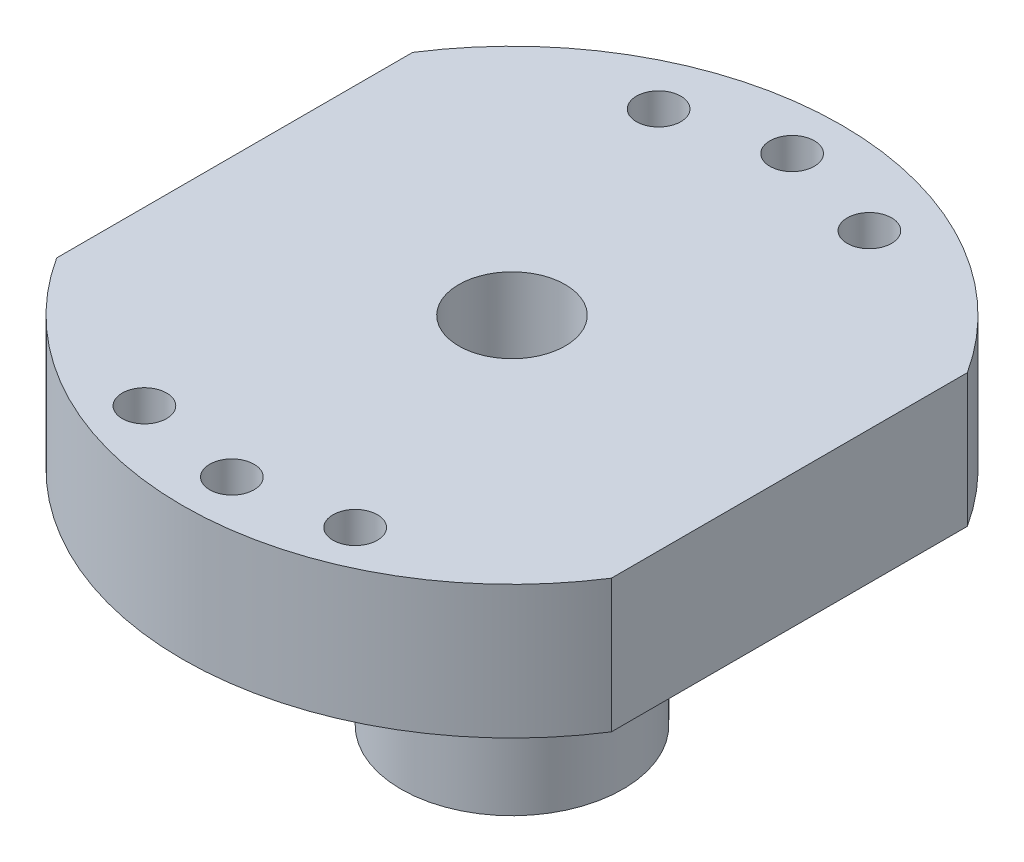
SolidWorks part; units mm, degrees
ref_plane "Front Plane" through (0, 0, 0) normal (0, 0, 1) x (1, 0, 0)
ref_plane "Top Plane" through (0, 0, 0) normal (0, 1, 0) x (1, 0, 0)
ref_plane "Right Plane" through (0, 0, 0) normal (1, 0, 0) x (0, 0, -1)
sketch "Sketch1" plane through (0, -18, 0) normal (0, -1, 0) x (1, 0, 0)
  line L1 (-23.4533, -87.6601) -> (26.5467, -87.6601)
  line L2 (-23.4533, -87.6601) -> (-23.4533, 12.3399)
  line L3 (-23.4533, 12.3399) -> (26.5467, 12.3399)
  line L4 (26.5467, -87.6601) -> (26.5467, 12.3399)
  circle A0 centre (1.5467, -37.6601) radius 29.705
  circle A1 centre (1.5467, -37.6601) radius 29.705 construction
  point P9 (1.5467, 12.3399)
  point P10 (-23.4533, -37.6601)
  circle M1 centre (-7.9533, -14.0266) radius 2
  circle M2 centre (11.0467, -14.0266) radius 2
  circle M3 centre (11.0467, -60.3766) radius 2
  circle M4 centre (-7.9533, -60.3766) radius 2
  circle M5 centre (1.5467, -62.9101) radius 2
  circle M6 centre (1.5467, -12.4101) radius 2
  line M11 (-13.578, -51.1251) -> (-13.578, -45.6601)
  line M12 (-13.578, -45.6601) -> (-17.0561, -45.6601)
  arc M13 (-17.0561, -45.6601) -> (-17.0561, -29.6601) centre (1.5467, -37.6601) cw
  line M14 (-17.0561, -29.6601) -> (-13.578, -29.6601)
  line M15 (-13.578, -29.6601) -> (-13.578, -24.1951)
  arc M16 (-13.578, -24.1951) -> (16.6713, -24.1951) centre (1.5467, -37.6601) cw
  line M17 (16.6713, -24.1951) -> (16.6713, -29.6601)
  line M18 (16.6713, -29.6601) -> (20.1494, -29.6601)
  line M19 (20.1494, -29.6601) -> (20.1494, -32.6601)
  line M20 (20.1494, -32.6601) -> (16.6713, -32.6601)
  line M21 (16.6713, -32.6601) -> (16.6713, -42.6601)
  line M22 (16.6713, -42.6601) -> (20.1494, -42.6601)
  line M23 (20.1494, -42.6601) -> (20.1494, -45.6601)
  line M24 (20.1494, -45.6601) -> (16.6713, -45.6601)
  line M25 (16.6713, -45.6601) -> (16.6713, -51.1251)
  arc M26 (16.6713, -51.1251) -> (-13.578, -51.1251) centre (1.5467, -37.6601) cw
  dimension "D1" = 50
  dimension "D2" = 100
extrude "Boss-Extrude1" add sketch "Sketch1" along normal blind 12 contours L4 A0 L2 M1 M3 M5 M26 M11 M12 M13 M14 M15 M16 M17 M18 M19 M20 M21 M22 M23 M24 M25 M6 M4 M2 | M11 M26 M25 M24 M23 M22 M21 M20 M19 M18 M17 M16 M15 M14 M13 M12
sketch "Sketch2" plane through (0, -30, 0) normal (0, -1, 0) x (1, 0, 0)
  circle A0 centre (1.5467, -37.6601) radius 4.8
  circle A1 centre (1.5467, -37.6601) radius 4.8 construction
extrude "Cut-Extrude1" cut sketch "Sketch2" against normal through all
sketch3d "3DSketch1"
  line L0 (1.5467, -30, -37.6601) -> (1.5467, -78.1853, -37.6601) construction
  line L1 (1.5467, -18, -37.6601) -> (1.5467, -30, -37.6601) construction
  line L2 (1.5467, -30, -37.6601) -> (1.5467, -30, 3.5909) construction
  line L3 (1.5467, -30, -32.8601) -> (1.5467, -45, -32.8601)
  line L4 (1.5467, -45, -32.8601) -> (1.5467, -45, -33.1601)
  line L5 (1.5467, -45, -33.1601) -> (1.5467, -50, -33.1601)
  line L7 (1.5467, -50, -33.1601) -> (1.5467, -50, -27.6601)
  line L8 (1.5467, -50, -27.6601) -> (1.5467, -30, -27.6601)
  line L9 (1.5467, -30, -27.6601) -> (1.5467, -30, -32.8601)
  dimension "D1" = 20
  dimension "D2" = 4.8
  dimension "D4" = 4.5
  dimension "D3" = 15
  dimension "D5" = 10
sketch "Sketch3" plane through (1.5467, 0, 0) normal (1, 0, 0) x (0, 0, -1)
  line L0 (27.6601, -50) -> (27.6601, -30) construction
  line L1 (33.1601, -50) -> (27.6601, -50) construction
  line L2 (33.1601, -45) -> (33.1601, -50) construction
  line L3 (32.8601, -45) -> (33.1601, -45) construction
  line L4 (32.8601, -30) -> (32.8601, -45) construction
  line L5 (27.6601, -30) -> (32.8601, -30) construction
  line L6 (27.6601, -50) -> (27.6601, -30)
  line L7 (33.1601, -50) -> (27.6601, -50)
  line L8 (33.1601, -45) -> (33.1601, -50)
  line L9 (32.8601, -45) -> (33.1601, -45)
  line L10 (32.8601, -30) -> (32.8601, -45)
  line L11 (27.6601, -30) -> (32.8601, -30)
revolve "Revolve1" add sketch "Sketch3" angle 360 about L0
chamfer "Chamfer1" distance 1 angle 45 1 edges at (1.5467, -50, -33.1601)
